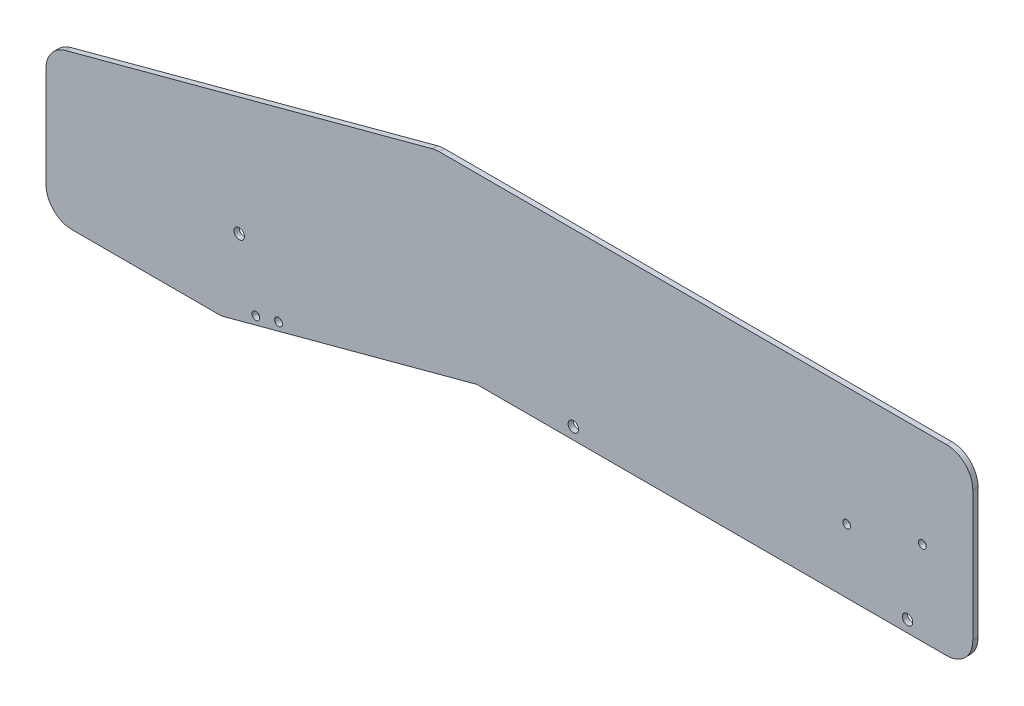
SolidWorks part; units mm, degrees
material "环氧树脂,未充填"
ref_plane "前视基准面" through (0, 0, 0) normal (0, 0, 1) x (1, 0, 0)
ref_plane "上视基准面" through (0, 0, 0) normal (0, 1, 0) x (1, 0, 0)
ref_plane "右视基准面" through (0, 0, 0) normal (1, 0, 0) x (0, 0, -1)
sketch "草图1" plane through (0, 0, 0) normal (0, 0, 1) x (1, 0, 0)
  line L1 (-177.5, 35) -> (177.5, 35)
  line L2 (-177.5, 35) -> (-177.5, -35)
  line L3 (-177.5, -35) -> (177.5, -35)
  line L4 (177.5, 35) -> (177.5, -35)
  line L5 (-177.5, 35) -> (177.5, -35) construction
  line L6 (-177.5, -35) -> (177.5, 35) construction
  point P0 (0, 0)
  dimension "D1" = 355
  dimension "D2" = 70
extrude "凸台-拉伸1" add sketch "草图1" along normal blind 2
sketch "草图2" plane through (0, 0, 2) normal (0, 0, 1) x (1, 0, 0)
  line L0 (-12.5, -35) -> (-177.5, -79.2116)
  line L1 (-177.5, -35) -> (177.5, -35) construction
  line L2 (-177.5, -79.2116) -> (-177.5, -35)
  line L3 (177.5, -35) -> (177.5, 35) construction
  line L4 (-177.5, -35) -> (-12.5, -35)
  dimension "D1" = 165
  dimension "D2" = 190
extrude "凸台-拉伸2" add sketch "草图2" against normal up to surface (2 mm away) up to face at (0, 0, 0)
sketch "草图3" plane through (0, 0, 2) normal (0, 0, 1) x (1, 0, 0)
  line L0 (-177.5, -30.5) -> (177.5, -30.5) construction
  line L1 (-177.5, 35) -> (-177.5, -79.2116) construction
  line L2 (177.5, -35) -> (177.5, 35) construction
  line L3 (177.5, 35) -> (-177.5, 35) construction
  circle A0 centre (152.5, -30.5) radius 2
  circle A1 centre (24.5, -30.5) radius 2
  circle A2 centre (-103.5, -30.5) radius 2
  dimension "D2" = 25
  dimension "D5" = 4
  dimension "D1" = 65.5
  dimension "D3" = 128
  dimension "D4" = 128
extrude "切除-拉伸1" cut sketch "草图3" against normal through all
sketch "草图4" plane through (0, 0, 2) normal (0, 0, 1) x (1, 0, 0)
  line L0 (-177.5, -79.2116) -> (-12.5, -35) construction
  line L1 (-177.5, -79.2116) -> (-12.5, -35)
  line L2 (-12.5, -35) -> (177.5, 15.9103) construction
  line L3 (177.5, -35) -> (177.5, 35) construction
  line L4 (177.5, 2.4518) -> (37.7281, -35) construction
  line L5 (-12.5, -35) -> (177.5, -35) construction
  line L6 (-177.5, -76.1058) -> (177.5, 19.0162) construction
  line L7 (-177.5, 35) -> (-177.5, -79.2116) construction
  circle A0 centre (158.1815, -2.7246) radius 1.5
  circle A1 centre (129.2037, -10.4892) radius 1.5
  circle A2 centre (-97.1275, -54.57) radius 1.5
  circle A3 centre (-88.4342, -52.2407) radius 1.5
  dimension "D1" = 30
  dimension "D2" = 3
  dimension "D6" = 9
  dimension "D8" = 3
  dimension "D3" = 20
  dimension "D4" = 13
  dimension "D5" = 15
  dimension "D7" = 271.5
  dimension "D9" = 3
extrude "切除-拉伸2" cut sketch "草图4" against normal through all contours A2 | A3 | A1 | A0
sketch "草图5" plane through (0, 0, 2) normal (0, 0, 1) x (1, 0, 0)
  line L0 (-177.5, -5) -> (-28.218, 35)
  line L1 (-177.5, 35) -> (-177.5, -79.2116) construction
  line L2 (177.5, 35) -> (-177.5, 35) construction
  line L3 (-28.218, 35) -> (-177.5, 35)
  line L4 (-177.5, 35) -> (-177.5, -5)
  line L5 (-177.5, -79.2116) -> (-12.5, -35) construction
  dimension "D1" = 40
extrude "切除-拉伸3" cut sketch "草图5" against normal up to surface (2 mm away) up to face at (-95.6275, -54.57, 0)
sketch "草图6" plane through (0, 0, 2) normal (0, 0, 1) x (1, 0, 0)
  line L0 (-110.3231, -61.2116) -> (-177.5, -61.2116)
  line L1 (-177.5, -79.2116) -> (-12.5, -35) construction
  line L2 (-177.5, -5) -> (-177.5, -79.2116) construction
  line L3 (-177.5, -61.2116) -> (-177.5, -79.2116)
  line L4 (-177.5, -79.2116) -> (-110.3231, -61.2116)
  dimension "D1" = 18
extrude "切除-拉伸4" cut sketch "草图6" against normal up to surface (2 mm away) up to face at (-95.6275, -54.57, 0)
fillet "圆角1" radius 10 5 edges at (177.5, 35, 1) (177.5, -35, 1) (-177.5, -5, 1) (-28.218, 35, 1) (-177.5, -61.2116, 1)
